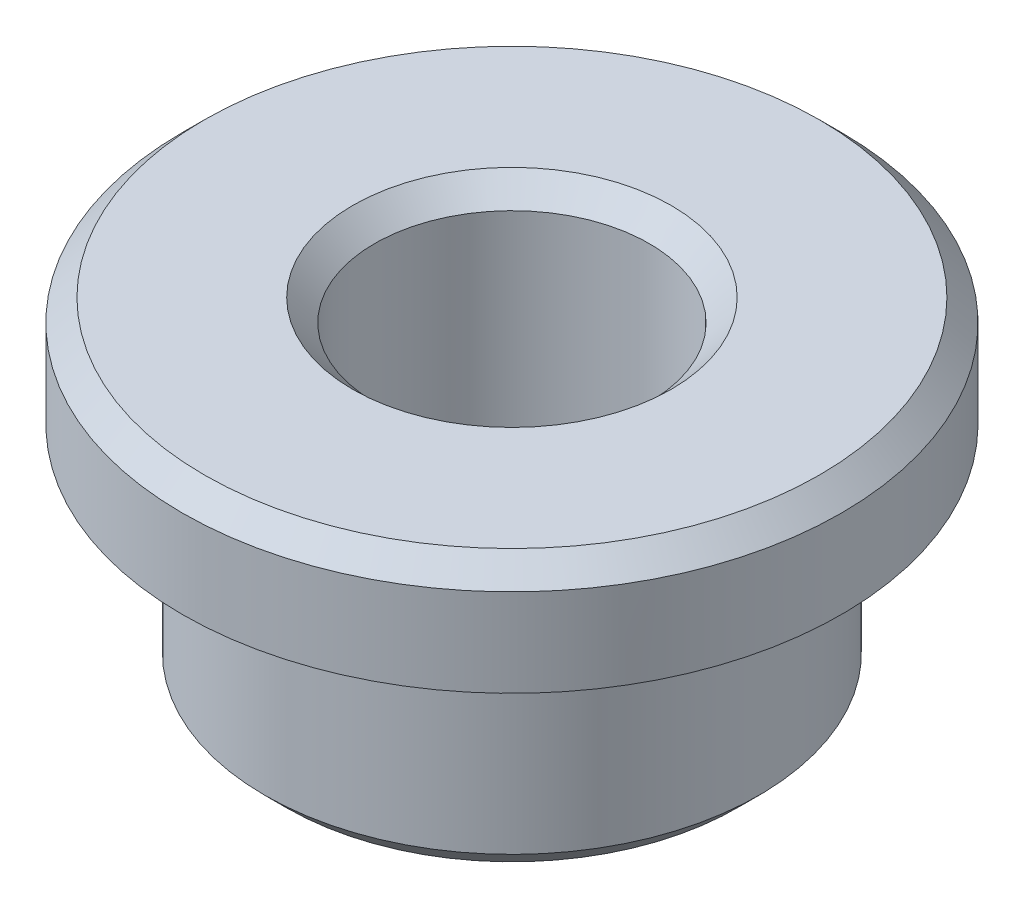
SolidWorks part; units mm, degrees
material "Brass"
ref_plane "Front" through (0, 0, 0) normal (0, 0, 1) x (1, 0, 0)
ref_plane "Top" through (0, 0, 0) normal (0, 1, 0) x (1, 0, 0)
ref_plane "Right" through (0, 0, 0) normal (1, 0, 0) x (0, 0, -1)
sketch "Sketch1" plane through (0, 0, 0) normal (1, 0, 0) x (0, 0, -1)
  line L0 (0, 6.7912) -> (0, 0) construction
  line L1 (1.25, 3) -> (1.25, 0)
  line L2 (1.25, 0) -> (2.25, 0)
  line L3 (2.25, 0) -> (2.25, 2)
  line L4 (2.25, 2) -> (3, 2)
  line L5 (3, 2) -> (3, 3)
  line L6 (3, 3) -> (1.25, 3)
  dimension "D1" = 2
  dimension "D2" = 2.5
  dimension "D3" = 4.5
  dimension "D4" = 1
  dimension "D5" = 6
revolve "Revolve1" add sketch "Sketch1" angle 360 about L0
cosmetic thread "Cosmetic Thread1" parameters "D1"=3, "D2"=3
chamfer "Chamfer1" distance 0.2 angle 45 3 edges at (0, 3, 1.25) (0, 3, 3) (0, 0, 2.25)
